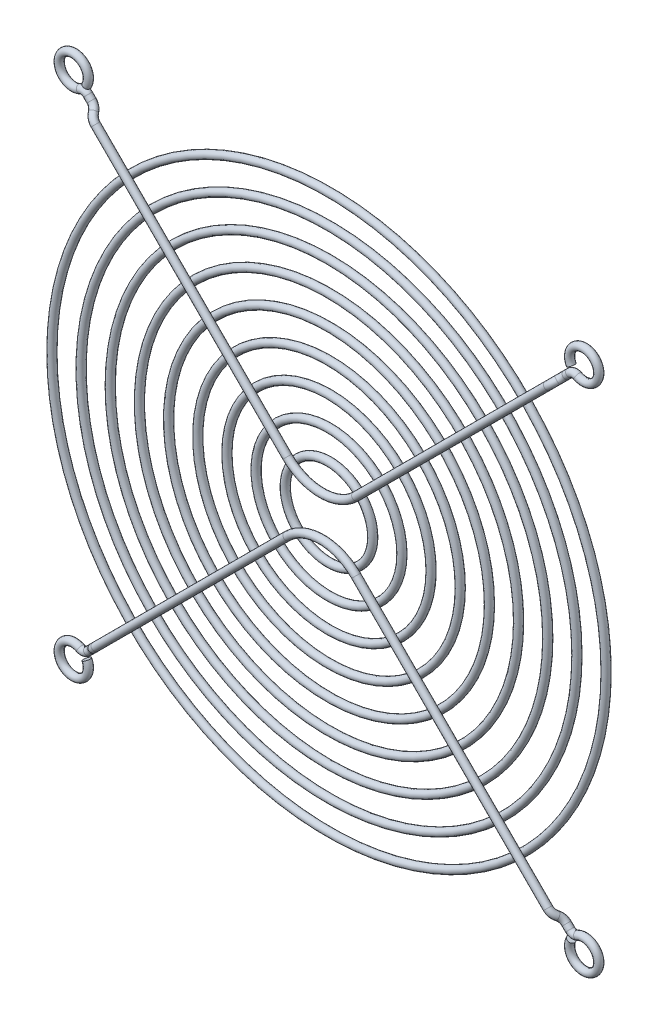
SolidWorks part; units mm, degrees
material "Cast Alloy Steel"
ref_plane "Front Plane" through (0, 0, 0) normal (0, 0, 1) x (1, 0, 0)
ref_plane "Top Plane" through (0, 0, 0) normal (0, 1, 0) x (1, 0, 0)
ref_plane "Right Plane" through (0, 0, 0) normal (1, 0, 0) x (0, 0, -1)
sketch "Sketch1" plane through (0, 0, 0) normal (0, 0, 1) x (1, 0, 0)
  line L0 (-9, 0) -> (-15, 0) construction
  line L1 (-15, 0) -> (-21, 0) construction
  line L2 (-21, 0) -> (-27, 0) construction
  line L3 (-27, 0) -> (-33, 0) construction
  line L4 (-33, 0) -> (-39, 0) construction
  line L5 (-39, 0) -> (-45, 0) construction
  line L6 (-45, 0) -> (-51, 0) construction
  line L7 (-51, 0) -> (-57, 0) construction
  circle A0 centre (0, 0) radius 9 construction
  circle A1 centre (0, 0) radius 15 construction
  circle A2 centre (0, 0) radius 21 construction
  circle A3 centre (0, 0) radius 27 construction
  circle A4 centre (0, 0) radius 33 construction
  circle A5 centre (0, 0) radius 39 construction
  circle A6 centre (0, 0) radius 45 construction
  circle A7 centre (0, 0) radius 51 construction
  circle A8 centre (0, 0) radius 57 construction
  dimension "D1" = 18
  dimension "D2" = 6
sketch "Sketch2" plane through (0, 0, 0) normal (0, 1, 0) x (1, 0, 0)
  circle A0 centre (-9, 0) radius 0.75
  dimension "D1" = 1.5
ref_axis "Axis1" through (0, 0, 2.4) along (0, 0, -1)
revolve "Revolve1" add sketch "Sketch2" angle 360 about axis through (0, 0, 2.4) along (0, 0, -1)
sketch "Sketch3" plane through (0, 0, 0) normal (0, 1, 0) x (1, 0, 0)
  circle A0 centre (-15, 0) radius 0.75
  dimension "D1" = 1.5
revolve "Revolve2" add sketch "Sketch3" angle 360 about axis through (0, 0, 2.4) along (0, 0, -1)
sketch "Sketch4" plane through (0, 0, 0) normal (0, 1, 0) x (1, 0, 0)
  circle A0 centre (-21, 0) radius 0.75
  dimension "D1" = 1.5
revolve "Revolve3" add sketch "Sketch4" angle 360 about axis through (0, 0, 2.4) along (0, 0, -1)
sketch "Sketch5" plane through (0, 0, 0) normal (0, 1, 0) x (1, 0, 0)
  circle A0 centre (-27, 0) radius 0.75
  dimension "D1" = 1.5
revolve "Revolve4" add sketch "Sketch5" angle 360 about axis through (0, 0, 2.4) along (0, 0, -1)
sketch "Sketch7" plane through (0, 0, 0) normal (0, 1, 0) x (1, 0, 0)
  circle A0 centre (-33, 0) radius 0.75
  dimension "D1" = 1.5
revolve "Revolve5" add sketch "Sketch7" angle 360 about axis through (0, 0, 2.4) along (0, 0, -1)
sketch "Sketch8" plane through (0, 0, 0) normal (0, 1, 0) x (1, 0, 0)
  circle A0 centre (-39, 0) radius 0.75
  dimension "D1" = 1.5
revolve "Revolve6" add sketch "Sketch8" angle 360 about axis through (0, 0, 2.4) along (0, 0, -1)
sketch "Sketch9" plane through (0, 0, 0) normal (0, 1, 0) x (1, 0, 0)
  circle A0 centre (-45, 0) radius 0.75
  dimension "D1" = 1.5
revolve "Revolve7" add sketch "Sketch9" angle 360 about axis through (0, 0, 2.4) along (0, 0, -1)
sketch "Sketch10" plane through (0, 0, 0) normal (0, 1, 0) x (1, 0, 0)
  circle A0 centre (-51, 0) radius 0.75
  dimension "D1" = 1.5
revolve "Revolve8" add sketch "Sketch10" angle 360 about axis through (0, 0, 2.4) along (0, 0, -1)
sketch "Sketch23" plane through (0, 0, 0) normal (0, 1, 0) x (1, 0, 0)
  circle A0 centre (-57, 0) radius 0.75
  dimension "D1" = 1.5
revolve "Revolve9" add sketch "Sketch23" angle 360 about axis through (0, 0, 2.4) along (0, 0, -1)
ref_plane "Plane1" through (0, 0, 1.5) normal (0, 0, 1) x (1, 0, 0)
sketch "Sketch11" plane through (0, 0, 1.5) normal (0, 0, 1) x (1, 0, 0)
  line L0 (-7.0711, 7.0711) -> (-39.598, 39.598)
  line L1 (0, 0) -> (0, 14.1421) construction
  line L2 (-7.0711, 7.0711) -> (0, 0) construction
  line L3 (-15, 0) -> (-21, 0) construction
  arc A0 (-7.0711, 7.0711) -> (0, 4.1421) centre (0, 14.1421) ccw
  dimension "D1" = 10
  dimension "D2" = 45
  dimension "D3" = 56
sketch "Sketch12" plane through (0, 0, 0) normal (1, 0, 0) x (0, 0, -1)
  circle A0 centre (-1.5, 4.1421) radius 0.75
  dimension "D1" = 1.5
sweep "Sweep1" add profiles "Sketch12" path "Sketch11"
ref_plane "Plane2" through (0, 0, 0) normal (0.7071, 0.7071, 0) x (0, 0, -1)
sketch "Sketch13" plane through (0, 0, 0) normal (0, 0, 1) x (1, 0, 0)
  line L0 (5.2385, -5.2385) -> (-5.2385, 5.2385) construction
  line L1 (0, 0) -> (-51.8183, 53.1817) construction
  line L2 (52.5, -52.5) -> (-52.5, -52.5) construction
  line L3 (52.5, -52.5) -> (52.5, 52.5) construction
  line L4 (52.5, 52.5) -> (-52.5, 52.5) construction
  line L5 (-52.5, -52.5) -> (-52.5, 52.5) construction
  line L6 (52.5, -52.5) -> (-52.5, 52.5) construction
  line L7 (52.5, 52.5) -> (-52.5, -52.5) construction
  line L8 (-51.8183, 53.1817) -> (-53.1817, 51.8183) construction
  line L9 (-53.1817, 51.8183) -> (0, 0) construction
  line L10 (-49.827, 51.138) -> (-52.5, 52.5) construction
  line L11 (-52.5, 52.5) -> (-51.138, 49.827) construction
  arc A0 (-49.827, 51.138) -> (-51.138, 49.827) centre (-52.5, 52.5) ccw
  circle A1 centre (0, 0) radius 74.2462 construction
  dimension "D2" = 6
  dimension "D1" = 105
  dimension "D3" = 18
sketch "Sketch14" plane through (0, 0, 0) normal (0.7071, 0.7071, 0) x (0, 0, -1)
  line L0 (0, 74.2462) -> (-4.5132, 74.2462) construction
ref_plane "Plane3" through (10.4161, 20.4427, 0) normal (0.454, 0.891, 0) x (0, 0, 1)
sketch "Sketch15" plane through (10.4161, 20.4427, 0) normal (0.454, 0.891, 0) x (0, 0, 1)
  circle A0 centre (0, -67.6123) radius 0.75
  dimension "D1" = 1.5
sweep "Sweep3" add profiles "Sketch15" path "Sketch13"
sketch "Sketch19" plane through (0, 0, 0) normal (0, 0, 1) x (1, 0, 0)
  line L0 (-50.7975, 49.1587) -> (-51.4785, 50.4952) construction
  line L1 (5.2385, -5.2385) -> (-5.2385, 5.2385) construction
  line L2 (-48.8731, 48.8731) -> (-49.5803, 49.5803)
  line L3 (-48.8731, 48.8731) -> (0, 0) construction
  arc A0 (-51.138, 49.827) -> (-49.5803, 49.5803) centre (-50.5289, 48.6316) cw
  arc A1 (-49.827, 51.138) -> (-51.138, 49.827) centre (-52.5, 52.5) ccw construction
  dimension "D1" = 1
sketch "Sketch20" plane through (-20.4427, -10.4161, 0) normal (0.891, 0.454, 0) x (0, 0, -1)
  circle A1 centre (0, 67.6123) radius 0.75
  circle A2 centre (0, 67.6123) radius 0.75
  dimension "D1" = 0
sweep "Sweep4" add profiles "Sketch20" path "Sketch19"
sketch "Sketch21" plane through (0, 0, 0) normal (0.7071, 0.7071, 0) x (0, 0, -1)
  line L0 (0, -74.2462) -> (0, 74.2462) construction
  line L1 (-1.5, 56) -> (-1.5, 65.808)
  line L3 (-0.75, 69.1171) -> (0.75, 69.1171) construction
  line L4 (-0.75, 69.1171) -> (0.75, 69.1171) construction
  line L5 (-0.75, 56) -> (-2.25, 56) construction
  line L6 (-0.75, 56) -> (-2.25, 56) construction
  arc A0 (0, 69.1171) -> (-0.75, 67.4625) centre (-2.2, 69.1171) cw
  arc A1 (-0.75, 67.4625) -> (-1.5, 65.808) centre (0.7, 65.808) ccw
  dimension "D1" = 2.2
sketch "Sketch22" plane through (-48.8731, 48.8731, 0) normal (0.7071, -0.7071, 0) x (0, 0, -1)
  circle A1 centre (0, 0) radius 0.75
  circle A2 centre (0, 0) radius 0.75
  dimension "D1" = 0
sweep "Sweep5" add profiles "Sketch22" path "Sketch21"
mirror "Mirror1" about plane through (0, 4.1421, 1.5) normal (1, 0, 0) of bodies 113
mirror "Mirror2" about plane through (0, 0, 0) normal (0, 1, 0) of bodies 114
